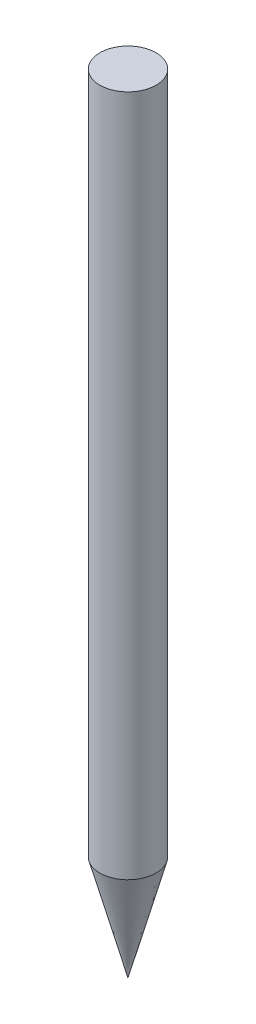
SolidWorks part; units mm, degrees
material "ABS"
ref_plane "Front Plane" through (0, 0, 0) normal (0, 0, 1) x (1, 0, 0)
ref_plane "Top Plane" through (0, 0, 0) normal (0, 1, 0) x (1, 0, 0)
ref_plane "Right Plane" through (0, 0, 0) normal (1, 0, 0) x (0, 0, -1)
sketch "Sketch1" plane through (0, 0, 0) normal (0, 1, 0) x (1, 0, 0)
  circle A0 centre (0, 0) radius 5
  dimension "D1" = 10
extrude "Boss-Extrude1" add sketch "Sketch1" along normal blind 140
chamfer "Chamfer1" distance 5 angle 75 1 edges at (0, 0, 5)
